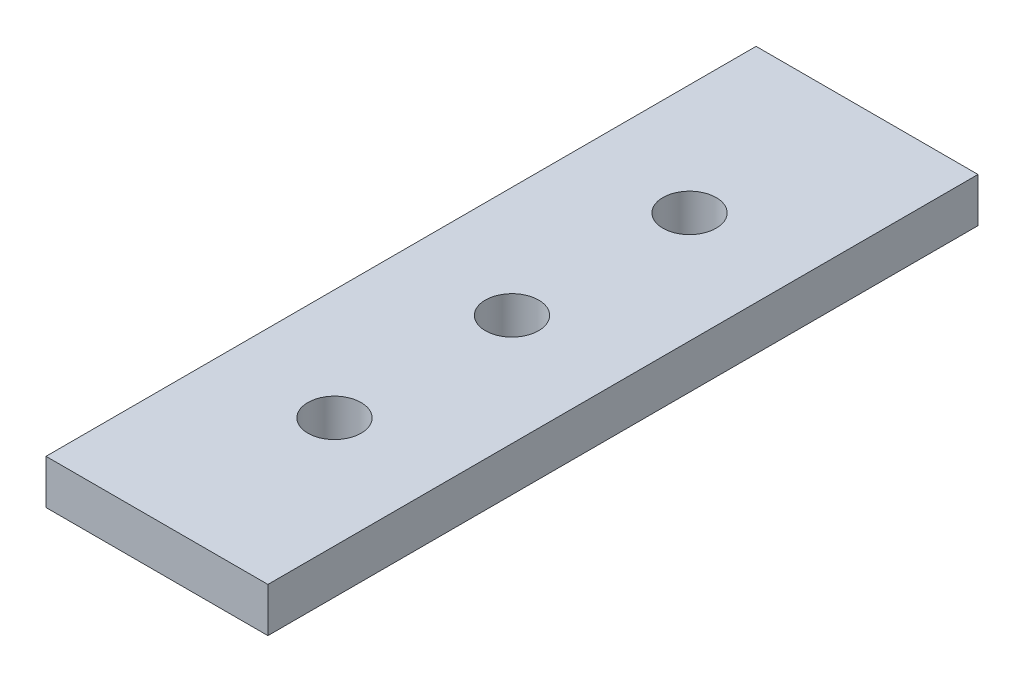
SolidWorks part; units mm, degrees
ref_plane "前视基准面" through (0, 0, 0) normal (0, 0, 1) x (1, 0, 0)
ref_plane "上视基准面" through (0, 0, 0) normal (0, 1, 0) x (1, 0, 0)
ref_plane "右视基准面" through (0, 0, 0) normal (1, 0, 0) x (0, 0, -1)
other "Configuration Table"
sketch "草图1" plane through (0, 0, 0) normal (0, 1, 0) x (1, 0, 0)
  line L0 (-25, 160) -> (-25, -16.7749) construction
  line L1 (0, 0) -> (-50, 0)
  line L2 (0, 0) -> (0, 160)
  line L3 (0, 160) -> (-50, 160)
  line L4 (-50, 0) -> (-50, 160)
  circle A0 centre (-25, 120) radius 6
  circle A1 centre (-25, 80) radius 6
  circle A2 centre (-25, 40) radius 6
  dimension "D3" = 12
  dimension "D4" = 12
  dimension "D5" = 12
  dimension "D7" = 40
  dimension "D8" = 40
  dimension "D1" = 160
  dimension "D2" = 50
  dimension "D6" = 40
extrude "凸台-拉伸1" add sketch "草图1" along normal blind 10
